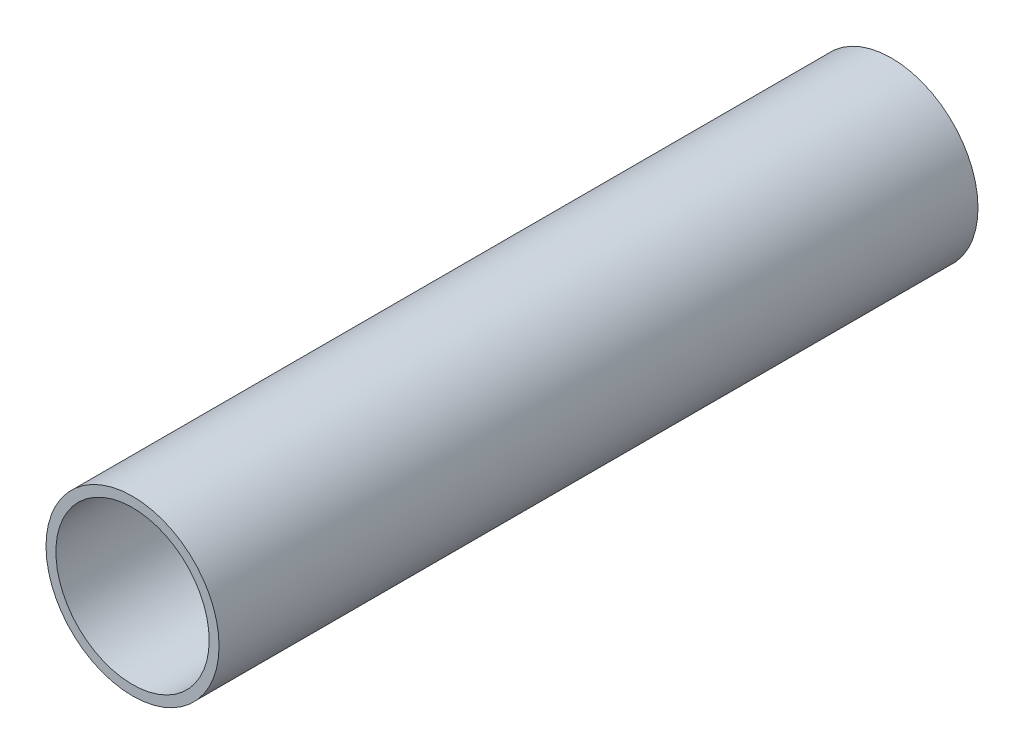
SolidWorks part; units mm, degrees
ref_plane "Plan de face" through (0, 0, 0) normal (0, 0, 1) x (1, 0, 0)
ref_plane "Plan de dessus" through (0, 0, 0) normal (0, 1, 0) x (1, 0, 0)
ref_plane "Plan de droite" through (0, 0, 0) normal (1, 0, 0) x (0, 0, -1)
sketch "Esquisse1" plane through (0, 0, 0) normal (0, 0, 1) x (1, 0, 0)
  circle A0 centre (0, 0) radius 50.5
  circle A1 centre (0, 0) radius 57
  dimension "D1" = 114
  dimension "D2" = 101
extrude "Boss.-Extru.1" add sketch "Esquisse1" along normal blind 500
